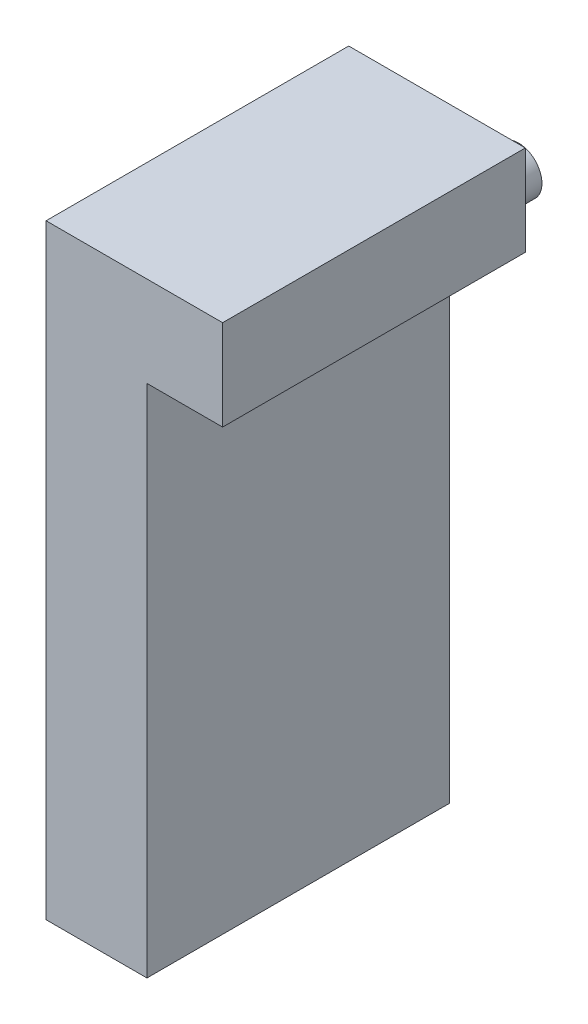
SolidWorks part; units mm, degrees
ref_plane "Front Plane" through (0, 0, 0) normal (0, 0, 1) x (1, 0, 0)
ref_plane "Top Plane" through (0, 0, 0) normal (0, 1, 0) x (1, 0, 0)
ref_plane "Right Plane" through (0, 0, 0) normal (1, 0, 0) x (0, 0, -1)
sketch "Sketch1" plane through (0, 0, 0) normal (0, 1, 0) x (1, 0, 0)
  line L1 (0, 0) -> (-20, 0)
  line L2 (0, 0) -> (0, 60)
  line L3 (0, 60) -> (-20, 60)
  line L4 (-20, 0) -> (-20, 60)
  dimension "D1" = 60
  dimension "D2" = 20
extrude "Boss-Extrude1" add sketch "Sketch1" along normal blind 120 contours L4 L3 L2 L1
sketch "Sketch2" plane through (0, 0, 0) normal (1, 0, 0) x (0, 0, -1)
  line L0 (60, 120) -> (60, 0) construction
  line L1 (0, 120) -> (60, 120)
  line L2 (0, 120) -> (0, 102.0782)
  line L3 (0, 102.0782) -> (60, 102.0782)
  line L4 (60, 120) -> (60, 102.0782)
extrude "Boss-Extrude2" add sketch "Sketch2" along normal blind 15
sketch "Sketch3" plane through (0, 0, -60) normal (0, 0, -1) x (-1, 0, 0)
  circle A0 centre (-8.6727, 110.5612) radius 4.625
  dimension "D1" = 9.25
extrude "Boss-Extrude3" add sketch "Sketch3" along normal blind 5
